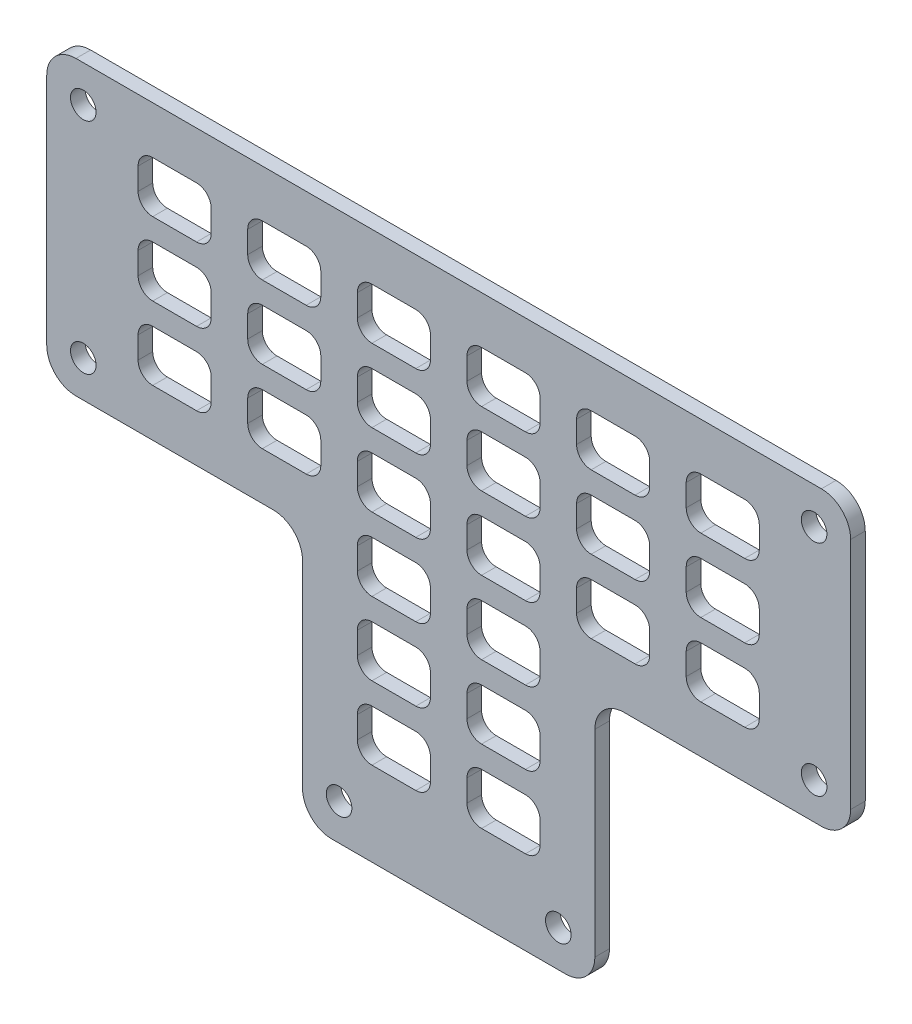
SolidWorks part; units mm, degrees
ref_plane "Front Plane" through (0, 0, 0) normal (0, 0, 1) x (1, 0, 0)
ref_plane "Top Plane" through (0, 0, 0) normal (0, 1, 0) x (1, 0, 0)
ref_plane "Right Plane" through (0, 0, 0) normal (1, 0, 0) x (0, 0, -1)
sketch "Sketch1" plane through (0, 0, 0) normal (0, 0, 1) x (1, 0, 0)
  line L0 (-20, -55) -> (-20, -20)
  line L1 (-55, 20) -> (55, 20)
  line L2 (-55, 20) -> (-55, -20)
  line L3 (-55, -20) -> (-20, -20)
  line L4 (55, 20) -> (55, -20)
  line L5 (-55, 20) -> (55, -20) construction
  line L6 (-55, -20) -> (55, 20) construction
  line L7 (-20, 0) -> (20, 0) construction
  line L8 (-20, 0) -> (-20, -55) construction
  line L9 (-20, -55) -> (20, -55)
  line L10 (20, 0) -> (20, -55) construction
  line L11 (20, -55) -> (20, -20)
  line L12 (20, -20) -> (55, -20)
  line L13 (-20, -20) -> (20, -20) construction
  point P0 (0, 0)
  dimension "D1" = 110
  dimension "D2" = 40
  dimension "D3" = 55
extrude "Boss-Extrude1" add sketch "Sketch1" along normal blind 2
fillet "Fillet1" radius 4 8 edges at (20, -20, 1) (20, -55, 1) (-20, -55, 1) (-20, -20, 1) (-55, -20, 1) (55, -20, 1) (55, 20, 1) (-55, 20, 1)
sketch "Sketch2" plane through (0, 0, 2) normal (0, 0, 1) x (1, 0, 0)
  line L1 (-50, 15) -> (50, 15) construction
  line L2 (-50, 15) -> (-50, -15) construction
  line L3 (-50, -15) -> (50, -15) construction
  line L4 (50, 15) -> (50, -15) construction
  line L5 (-50, 15) -> (50, -15) construction
  line L6 (-50, -15) -> (50, 15) construction
  line L7 (15, 50) -> (-15, 50) construction
  line L8 (15, 50) -> (15, -50) construction
  line L9 (15, -50) -> (-15, -50) construction
  line L10 (-15, 50) -> (-15, -50) construction
  line L11 (15, 50) -> (-15, -50) construction
  line L12 (15, -50) -> (-15, 50) construction
  circle A0 centre (-50, 15) radius 1.75
  circle A1 centre (-50, -15) radius 1.75
  circle A2 centre (-15, -50) radius 1.75
  circle A3 centre (15, -50) radius 1.75
  circle A4 centre (50, -15) radius 1.75
  circle A5 centre (50, 15) radius 1.75
  point P0 (0, 0)
  point P6 (0, 0)
  dimension "D1" = 3.5
  dimension "D2" = 100
  dimension "D3" = 30
extrude "Cut-Extrude1" cut sketch "Sketch2" against normal through all
sketch "Sketch3" plane through (0, 0, 2) normal (0, 0, 1) x (1, 0, 0)
  line L0 (-55, 16) -> (-55, -16) construction
  line L1 (-40.5, 13.5) -> (-34.5, 13.5)
  line L2 (-42.5, 11.5) -> (-42.5, 8.5)
  line L3 (-40.5, 6.5) -> (-34.5, 6.5)
  line L4 (-32.5, 11.5) -> (-32.5, 8.5)
  line L5 (-42.5, 13.5) -> (-32.5, 6.5) construction
  line L6 (-42.5, 6.5) -> (-32.5, 13.5) construction
  line L7 (51, 20) -> (-51, 20) construction
  arc A0 (-34.5, 6.5) -> (-32.5, 8.5) centre (-34.5, 8.5) ccw
  arc A1 (-34.5, 13.5) -> (-32.5, 11.5) centre (-34.5, 11.5) cw
  arc A2 (-40.5, 13.5) -> (-42.5, 11.5) centre (-40.5, 11.5) ccw
  arc A3 (-42.5, 8.5) -> (-40.5, 6.5) centre (-40.5, 8.5) ccw
  point P0 (-37.5, 10)
  dimension "D3" = 2
  dimension "D1" = 10
  dimension "D2" = 7
  dimension "D4" = 17.5
  dimension "D5" = 10
extrude "Cut-Extrude2" cut sketch "Sketch3" against normal through all
pattern_linear "LPattern1" count 6 spacing 15 along (1, 0, 0) count 3 spacing 10 along (0, -1, 0) of "Cut-Extrude2"
sketch "Sketch4" plane through (0, 0, 2) normal (0, 0, 1) x (1, 0, 0)
  line L0 (-12.5, -8.5) -> (-12.5, -11.5) construction
  line L1 (-10.5, -13.5) -> (-4.5, -13.5) construction
  line L2 (-2.5, -11.5) -> (-2.5, -8.5) construction
  line L3 (-4.5, -6.5) -> (-10.5, -6.5) construction
  line L4 (-12.5, -8.5) -> (-12.5, -11.5) construction
  line L5 (-10.5, -13.5) -> (-4.5, -13.5) construction
  line L6 (-2.5, -11.5) -> (-2.5, -8.5) construction
  line L7 (-4.5, -6.5) -> (-10.5, -6.5) construction
  line L8 (2.5, -8.5) -> (2.5, -11.5) construction
  line L9 (4.5, -13.5) -> (10.5, -13.5) construction
  line L10 (12.5, -11.5) -> (12.5, -8.5) construction
  line L11 (10.5, -6.5) -> (4.5, -6.5) construction
  line L12 (2.5, -18.5) -> (2.5, -21.5)
  line L13 (4.5, -23.5) -> (10.5, -23.5)
  line L14 (12.5, -21.5) -> (12.5, -18.5)
  line L15 (10.5, -16.5) -> (4.5, -16.5)
  line L16 (2.5, -28.5) -> (2.5, -31.5)
  line L17 (4.5, -33.5) -> (10.5, -33.5)
  line L18 (12.5, -31.5) -> (12.5, -28.5)
  line L19 (10.5, -26.5) -> (4.5, -26.5)
  line L20 (2.5, -38.5) -> (2.5, -41.5)
  line L21 (4.5, -43.5) -> (10.5, -43.5)
  line L22 (12.5, -41.5) -> (12.5, -38.5)
  line L23 (10.5, -36.5) -> (4.5, -36.5)
  line L24 (-12.5, -18.5) -> (-12.5, -21.5)
  line L25 (-10.5, -23.5) -> (-4.5, -23.5)
  line L26 (-2.5, -21.5) -> (-2.5, -18.5)
  line L27 (-4.5, -16.5) -> (-10.5, -16.5)
  line L28 (-12.5, -28.5) -> (-12.5, -31.5)
  line L29 (-10.5, -33.5) -> (-4.5, -33.5)
  line L30 (-2.5, -31.5) -> (-2.5, -28.5)
  line L31 (-4.5, -26.5) -> (-10.5, -26.5)
  line L32 (-12.5, -38.5) -> (-12.5, -41.5)
  line L33 (-10.5, -43.5) -> (-4.5, -43.5)
  line L34 (-2.5, -41.5) -> (-2.5, -38.5)
  line L35 (-4.5, -36.5) -> (-10.5, -36.5)
  arc A0 (-10.5, -6.5) -> (-12.5, -8.5) centre (-10.5, -8.5) ccw construction
  arc A1 (-12.5, -11.5) -> (-10.5, -13.5) centre (-10.5, -11.5) ccw construction
  arc A2 (-4.5, -13.5) -> (-2.5, -11.5) centre (-4.5, -11.5) ccw construction
  arc A3 (-2.5, -8.5) -> (-4.5, -6.5) centre (-4.5, -8.5) ccw construction
  arc A4 (-10.5, -6.5) -> (-12.5, -8.5) centre (-10.5, -8.5) ccw construction
  arc A5 (-12.5, -11.5) -> (-10.5, -13.5) centre (-10.5, -11.5) ccw construction
  arc A6 (-4.5, -13.5) -> (-2.5, -11.5) centre (-4.5, -11.5) ccw construction
  arc A7 (-2.5, -8.5) -> (-4.5, -6.5) centre (-4.5, -8.5) ccw construction
  arc A8 (4.5, -6.5) -> (2.5, -8.5) centre (4.5, -8.5) ccw construction
  arc A9 (2.5, -11.5) -> (4.5, -13.5) centre (4.5, -11.5) ccw construction
  arc A10 (10.5, -13.5) -> (12.5, -11.5) centre (10.5, -11.5) ccw construction
  arc A11 (12.5, -8.5) -> (10.5, -6.5) centre (10.5, -8.5) ccw construction
  arc A12 (4.5, -16.5) -> (2.5, -18.5) centre (4.5, -18.5) ccw
  arc A13 (2.5, -21.5) -> (4.5, -23.5) centre (4.5, -21.5) ccw
  arc A14 (10.5, -23.5) -> (12.5, -21.5) centre (10.5, -21.5) ccw
  arc A15 (12.5, -18.5) -> (10.5, -16.5) centre (10.5, -18.5) ccw
  arc A16 (4.5, -26.5) -> (2.5, -28.5) centre (4.5, -28.5) ccw
  arc A17 (2.5, -31.5) -> (4.5, -33.5) centre (4.5, -31.5) ccw
  arc A18 (10.5, -33.5) -> (12.5, -31.5) centre (10.5, -31.5) ccw
  arc A19 (12.5, -28.5) -> (10.5, -26.5) centre (10.5, -28.5) ccw
  arc A20 (4.5, -36.5) -> (2.5, -38.5) centre (4.5, -38.5) ccw
  arc A21 (2.5, -41.5) -> (4.5, -43.5) centre (4.5, -41.5) ccw
  arc A22 (10.5, -43.5) -> (12.5, -41.5) centre (10.5, -41.5) ccw
  arc A23 (12.5, -38.5) -> (10.5, -36.5) centre (10.5, -38.5) ccw
  arc A24 (-10.5, -16.5) -> (-12.5, -18.5) centre (-10.5, -18.5) ccw
  arc A25 (-12.5, -21.5) -> (-10.5, -23.5) centre (-10.5, -21.5) ccw
  arc A26 (-4.5, -23.5) -> (-2.5, -21.5) centre (-4.5, -21.5) ccw
  arc A27 (-2.5, -18.5) -> (-4.5, -16.5) centre (-4.5, -18.5) ccw
  arc A28 (-10.5, -26.5) -> (-12.5, -28.5) centre (-10.5, -28.5) ccw
  arc A29 (-12.5, -31.5) -> (-10.5, -33.5) centre (-10.5, -31.5) ccw
  arc A30 (-4.5, -33.5) -> (-2.5, -31.5) centre (-4.5, -31.5) ccw
  arc A31 (-2.5, -28.5) -> (-4.5, -26.5) centre (-4.5, -28.5) ccw
  arc A32 (-10.5, -36.5) -> (-12.5, -38.5) centre (-10.5, -38.5) ccw
  arc A33 (-12.5, -41.5) -> (-10.5, -43.5) centre (-10.5, -41.5) ccw
  arc A34 (-4.5, -43.5) -> (-2.5, -41.5) centre (-4.5, -41.5) ccw
  arc A35 (-2.5, -38.5) -> (-4.5, -36.5) centre (-4.5, -38.5) ccw
  dimension "D1" = 2
  dimension "D2" = 4
extrude "Cut-Extrude3" cut sketch "Sketch4" against normal through all
